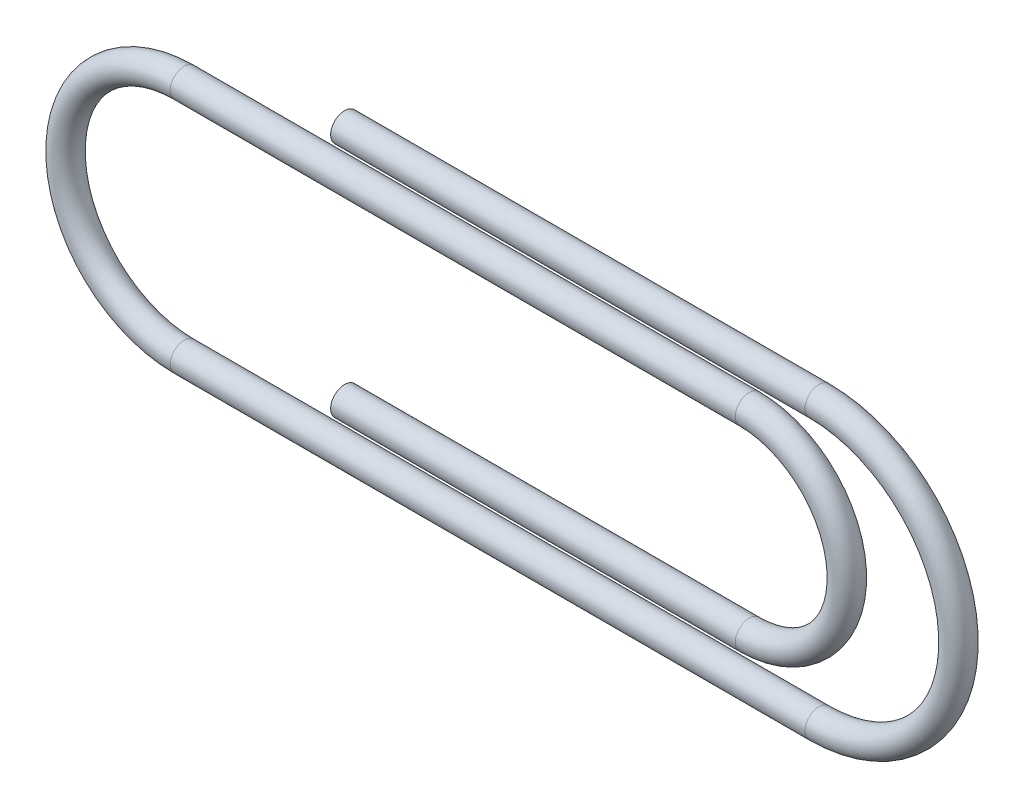
SolidWorks part; units mm, degrees
ref_plane "Front Plane" through (0, 0, 0) normal (0, 0, 1) x (1, 0, 0)
ref_plane "Top Plane" through (0, 0, 0) normal (0, 1, 0) x (1, 0, 0)
ref_plane "Right Plane" through (0, 0, 0) normal (1, 0, 0) x (0, 0, -1)
sketch "Sketch1" plane through (0, 0, 0) normal (0, 0, 1) x (1, 0, 0)
  line L0 (0, 0) -> (14.5, 0)
  line L1 (14.5, 0) -> (14.5, 7) construction
  line L2 (14.5, 7) -> (-5.75, 7)
  line L3 (-5.75, 7) -> (-5.75, -1.5) construction
  line L4 (-5.75, -1.5) -> (17, -1.5)
  line L5 (17, -1.5) -> (17, 8.5) construction
  line L6 (17, 8.5) -> (0, 8.5)
  arc A0 (14.5, 7) -> (14.5, 0) centre (14.5, 3.5) cw
  arc A1 (17, 8.5) -> (17, -1.5) centre (17, 3.5) cw
  arc A2 (-5.75, 7) -> (-5.75, -1.5) centre (-5.75, 2.75) ccw
  point P12 (-10, 2.75)
  point P13 (18, 3.5)
  point P14 (22, 3.5)
  dimension "D6" = 10
  dimension "D5" = 3.5
  dimension "D1" = 32
  dimension "D2" = 4
  dimension "D3" = 1.5
  dimension "D4" = 1.5
sketch "Sketch7" plane through (0, 0, 0) normal (1, 0, 0) x (0, 0, -1)
  circle A0 centre (0, 0) radius 0.5
  dimension "D1" = 1
sweep "Sweep1" add profiles "Sketch7" path "Sketch1"
